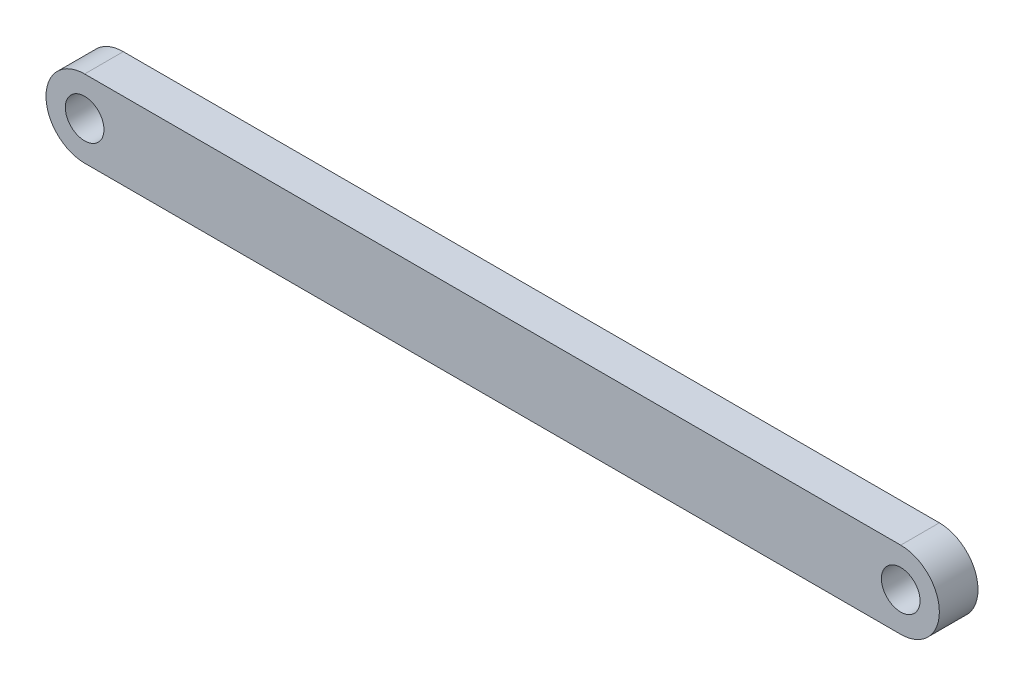
SolidWorks part; units mm, degrees
ref_plane "前基準面" through (0, 0, 0) normal (0, 0, 1) x (1, 0, 0)
ref_plane "上基準面" through (0, 0, 0) normal (0, 1, 0) x (1, 0, 0)
ref_plane "右基準面" through (0, 0, 0) normal (1, 0, 0) x (0, 0, -1)
sketch "草圖1" plane through (0, 0, 0) normal (0, 0, 1) x (1, 0, 0)
  line L0 (-21.12, 2.0011) -> (21.12, 2.0011)
  line L1 (-21.12, -1.9989) -> (21.12, -1.9989)
  arc A0 (-21.12, 2.0011) -> (-21.12, -1.9989) centre (-21.12, 0.0011) ccw
  arc A1 (21.12, -1.9989) -> (21.12, 2.0011) centre (21.12, 0.0011) ccw
  circle A2 centre (-21.12, 0.0011) radius 1
  circle A3 centre (21.12, 0.0011) radius 1
  dimension "D1" = 42.24
  dimension "D2" = 2
  dimension "D3" = 2
  dimension "D4" = 2
  dimension "D5" = 21.12
extrude "填料-伸長1" add sketch "草圖1" along normal blind 2
